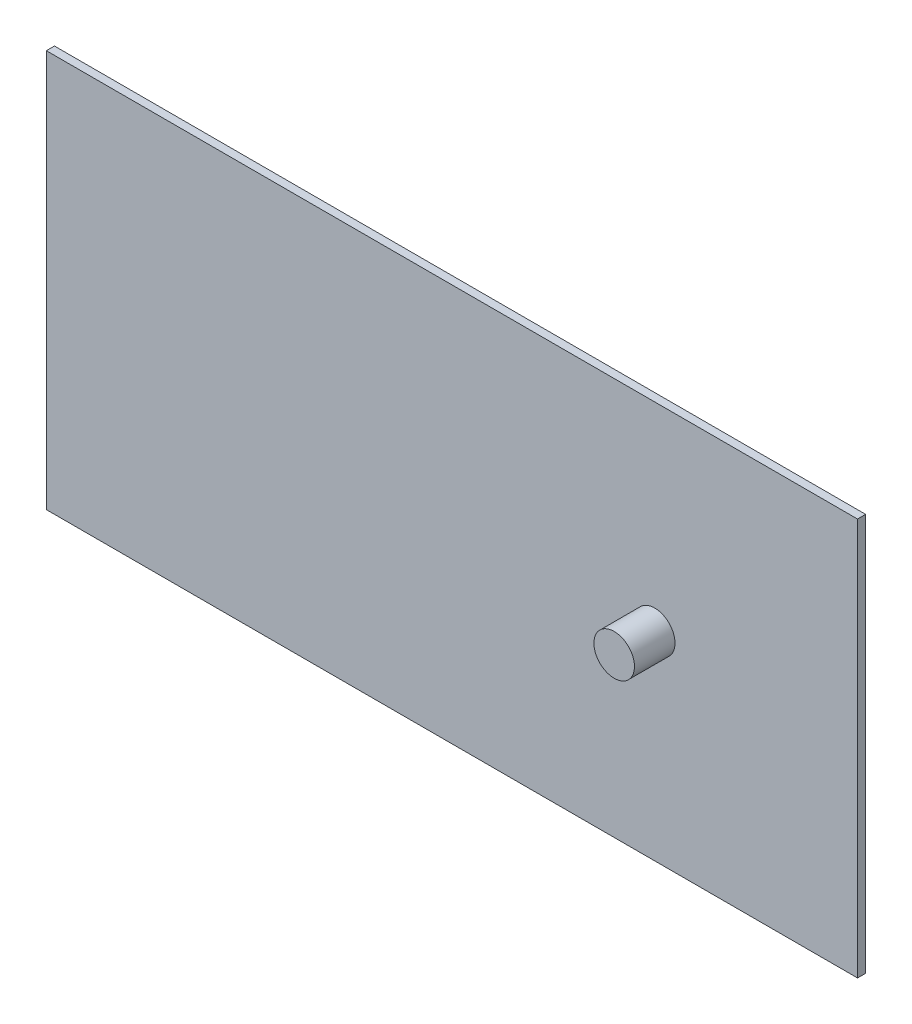
SolidWorks part; units mm, degrees
ref_plane "Front Plane" through (0, 0, 0) normal (0, 0, 1) x (1, 0, 0)
ref_plane "Top Plane" through (0, 0, 0) normal (0, 1, 0) x (1, 0, 0)
ref_plane "Right Plane" through (0, 0, 0) normal (1, 0, 0) x (0, 0, -1)
sketch "草图1" plane through (0, 0, 0) normal (0, 0, 1) x (1, 0, 0)
  line L1 (100, 49) -> (-100, 49)
  line L2 (100, 49) -> (100, -49)
  line L3 (100, -49) -> (-100, -49)
  line L4 (-100, 49) -> (-100, -49)
  line L5 (100, 49) -> (-100, -49) construction
  line L6 (100, -49) -> (-100, 49) construction
  point P0 (0, 0)
  dimension "D1" = 200
  dimension "D2" = 98
extrude "凸台-拉伸1" add sketch "草图1" along normal blind 2
sketch "草图2" plane through (0, 0, 2) normal (0, 0, 1) x (1, 0, 0)
  line L0 (0, 0) -> (100, 0)
  line L1 (100, -49) -> (100, 49) construction
  circle A0 centre (50, 0) radius 5
  dimension "D1" = 10
extrude "凸台-拉伸2" add sketch "草图2" along normal blind 10 contours A0
